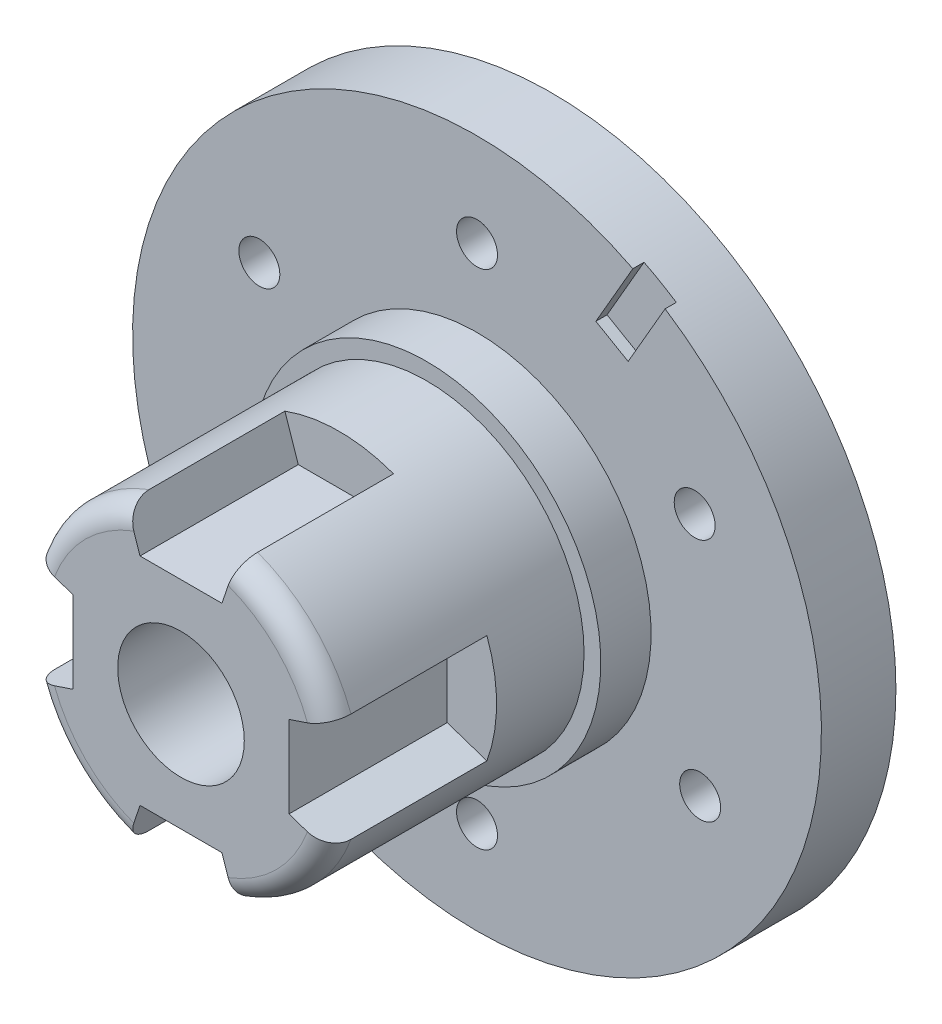
SolidWorks part; units mm, degrees
ref_plane "Спереди" through (0, 0, 0) normal (0, 0, 1) x (1, 0, 0)
ref_plane "Сверху" through (0, 0, 0) normal (0, 1, 0) x (1, 0, 0)
ref_plane "Справа" through (0, 0, 0) normal (1, 0, 0) x (0, 0, -1)
sketch "Эскиз1" plane through (0, 0, 0) normal (0, 0, 1) x (1, 0, 0)
  line L0 (0, 0) -> (0, 13.5) construction
  line L1 (0, 0) -> (-11.9855, -6.2127) construction
  line L2 (0, 0) -> (11.9855, -6.2127) construction
  circle A0 centre (0, 13.5) radius 1.1
  circle A1 centre (-11.9855, -6.2127) radius 1.1
  circle A2 centre (11.9855, -6.2127) radius 1.1
  circle A3 centre (0, 0) radius 18.5
  dimension "D4" = 2.2
  dimension "D5" = 37
  dimension "D1" = 13.5
  dimension "D2" = 117.4
  dimension "D3" = 117.4
extrude "Бобышка-Вытянуть1" add sketch "Эскиз1" along normal blind 4
sketch "Эскиз2" plane through (0, 0, 0) normal (0, 0, -1) x (-1, 0, 0)
  circle A0 centre (0, 13.5) radius 1.1
  circle A1 centre (11.9855, -6.2127) radius 1.1
  circle A2 centre (-11.9855, -6.2127) radius 1.1
  circle A3 centre (0, 13.5) radius 3
  circle A4 centre (11.9855, -6.2127) radius 3
  circle A5 centre (-11.9855, -6.2127) radius 3
  dimension "D1" = 2.2
  dimension "D2" = 6
extrude "Бобышка-Вытянуть2" [suppressed] add sketch "Эскиз2" along normal blind 1.2
sketch "Эскиз3" plane through (0, 0, 4) normal (0, 0, 1) x (1, 0, 0)
  circle A0 centre (0, 0) radius 8.45
  dimension "D1" = 16.9
extrude "Бобышка-Вытянуть3" add sketch "Эскиз3" along normal blind 15.9
fillet "Скругление1" radius 1.2 1 edges at (8.45, 0, 19.9)
sketch "Эскиз4" plane through (0, 0, 19.9) normal (0, 0, 1) x (1, 0, 0)
  line L0 (0, 0) -> (0, 5.8) construction
  line L1 (-2.2, 5.8) -> (-2.9319, 7.9784)
  line L2 (2.2, 5.8) -> (2.9319, 7.9784)
  line L3 (-2.2, 5.8) -> (2.2, 5.8)
  line L13 (5.8, 2.2) -> (7.9784, 2.9319)
  line L14 (5.8, -2.2) -> (7.9784, -2.9319)
  line L15 (5.8, 2.2) -> (5.8, -2.2)
  line L16 (0, 0) -> (5.8, 0) construction
  line L17 (2.2, -5.8) -> (2.9319, -7.9784)
  line L18 (-2.2, -5.8) -> (-2.9319, -7.9784)
  line L19 (2.2, -5.8) -> (-2.2, -5.8)
  line L20 (0, 0) -> (0, -5.8) construction
  line L21 (-5.8, -2.2) -> (-7.9784, -2.9319)
  line L22 (-5.8, 2.2) -> (-7.9784, 2.9319)
  line L23 (-5.8, -2.2) -> (-5.8, 2.2)
  line L24 (0, 0) -> (-5.8, 0) construction
  arc A0 (2.9319, 7.9784) -> (-2.9319, 7.9784) centre (0, 0) ccw
  arc A4 (7.9784, -2.9319) -> (7.9784, 2.9319) centre (0, 0) ccw
  arc A5 (-2.9319, -7.9784) -> (2.9319, -7.9784) centre (0, 0) ccw
  arc A6 (-7.9784, 2.9319) -> (-7.9784, -2.9319) centre (0, 0) ccw
  point P14 (5.0261, 2.6522)
  point P15 (5.0261, 2.6522)
  point P16 (-2.6522, 5.0261)
  point P19 (-2.6522, 5.0261)
  point P24 (2.6522, -5.0261)
  point P25 (2.6522, -5.0261)
  point P31 (-5.0261, -2.6522)
  point P32 (-5.0261, -2.6522)
  point P33 (0, 0)
  dimension "D1" = 17
  dimension "D2" = 4.4
  dimension "D3" = 108.571
  dimension "D4" = 5.8
  dimension "D5" = 37.141
  dimension "D6" = 4
extrude "Вырез-Вытянуть1" cut sketch "Эскиз4" against normal blind 8.5
sketch "Эскиз5" plane through (0, 0, 4) normal (0, 0, 1) x (1, 0, 0)
  circle A0 centre (0, 0) radius 9.35
  dimension "D1" = 18.7
extrude "Бобышка-Вытянуть4" add sketch "Эскиз5" along normal blind 2.7
sketch "Эскиз6" plane through (0, 0, 0) normal (0, 0, -1) x (-1, 0, 0)
  line L0 (0, 0) -> (0, -13.5) construction
  line L1 (0, 0) -> (11.6913, 6.75) construction
  line L2 (0, 0) -> (-11.6913, 6.75) construction
  circle A0 centre (-11.6913, 6.75) radius 1.1
  circle A1 centre (11.6913, 6.75) radius 1.1
  circle A2 centre (0, -13.5) radius 1.1
  dimension "D4" = 2.2
  dimension "D1" = 13.5
  dimension "D2" = 120
  dimension "D3" = 120
extrude "Вырез-Вытянуть2" cut sketch "Эскиз6" against normal through all
sketch "Эскиз7" plane through (0, 0, 19.9) normal (0, 0, 1) x (1, 0, 0)
  circle A0 centre (0, 0) radius 3.4
  dimension "D1" = 6.8
extrude "Вырез-Вытянуть3" cut sketch "Эскиз7" against normal blind 6.5
sketch "Эскиз8" plane through (0, 0, 0) normal (0, 0, 1) x (1, 0, 0)
  line L0 (0, 0) -> (0, 25.3988) construction
  line L1 (0, 0) -> (11.7334, 20.3229) construction
  line L3 (8.116, 12.0574) -> (10.116, 15.5215)
  line L4 (8.116, 12.0574) -> (6.384, 13.0574)
  line L5 (6.384, 13.0574) -> (8.384, 16.5215)
  line L6 (10.116, 15.5215) -> (8.384, 16.5215)
  line L7 (8.116, 12.0574) -> (8.384, 16.5215) construction
  line L8 (6.384, 13.0574) -> (10.116, 15.5215) construction
  point P3 (8.25, 14.2894)
  dimension "D1" = 30
  dimension "D2" = 2
  dimension "D3" = 4
  dimension "D4" = 16.5
extrude "Вырез-Вытянуть5" cut sketch "Эскиз8" against normal blind 0.6 from surface at 4 starting at face at (12.7913, 6.75, 4)
